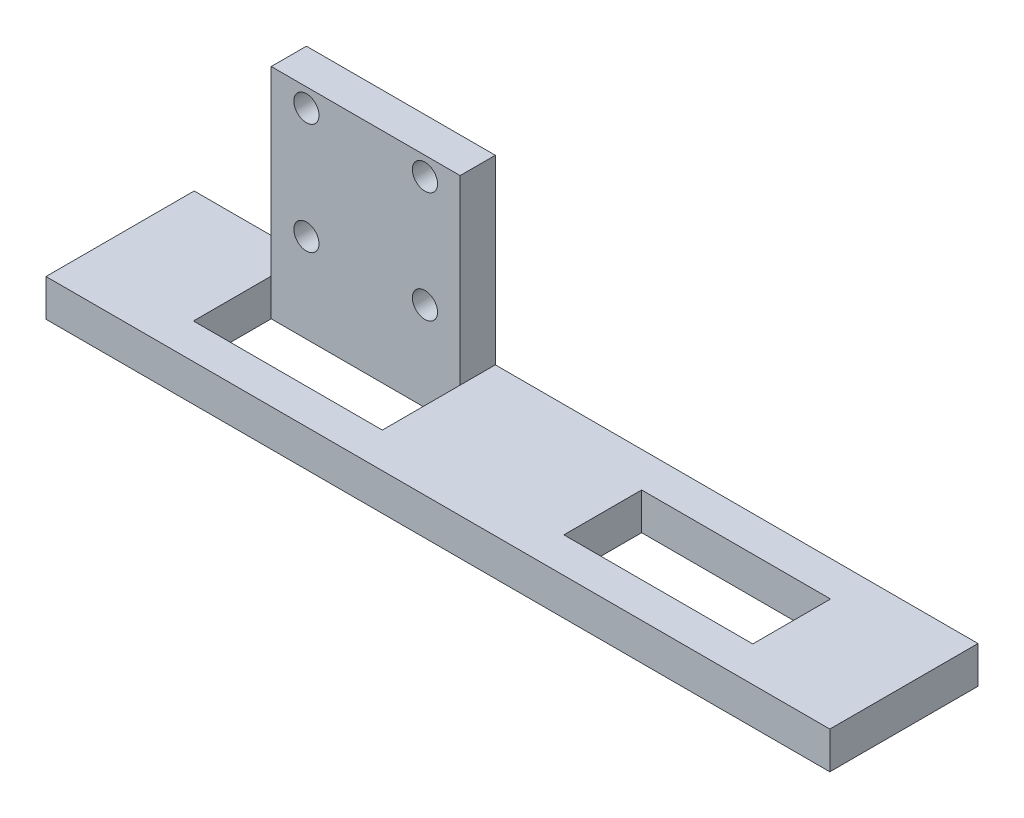
SolidWorks part; units mm, degrees
ref_plane "Front Plane" through (0, 0, 0) normal (0, 0, 1) x (1, 0, 0)
ref_plane "Top Plane" through (0, 0, 0) normal (0, 1, 0) x (1, 0, 0)
ref_plane "Right Plane" through (0, 0, 0) normal (1, 0, 0) x (0, 0, -1)
sketch "Sketch1" plane through (0, 0, 0) normal (0, 1, 0) x (1, 0, 0)
  line L0 (0, 10) -> (0, -10) construction
  line L1 (52.9, -10) -> (-52.9, -10)
  line L2 (52.9, -10) -> (52.9, 10)
  line L3 (52.9, 10) -> (-52.9, 10)
  line L4 (-52.9, -10) -> (-52.9, 10)
  line L5 (52.9, -10) -> (-52.9, 10) construction
  line L6 (52.9, 10) -> (-52.9, -10) construction
  line L7 (12.25, 5.25) -> (37.75, 5.25)
  line L8 (12.25, 5.25) -> (12.25, -5.25)
  line L9 (12.25, -5.25) -> (37.75, -5.25)
  line L10 (37.75, 5.25) -> (37.75, -5.25)
  line L11 (12.25, 5.25) -> (37.75, -5.25) construction
  line L12 (12.25, -5.25) -> (37.75, 5.25) construction
  line L13 (-37.75, 5.25) -> (-37.75, -5.25)
  line L14 (-12.25, 5.25) -> (-12.25, -5.25)
  line L15 (-12.25, 5.25) -> (-37.75, 5.25)
  line L16 (-12.25, -5.25) -> (-37.75, -5.25)
  point P0 (0, 0)
  point P6 (25, 0)
  dimension "D1" = 105.8
  dimension "D2" = 20
  dimension "D3" = 25.5
  dimension "D4" = 10.5
  dimension "D5" = 15.15
  dimension "D6" = 4.75
extrude "Boss-Extrude1" add sketch "Sketch1" along normal blind 5
sketch "Sketch2" plane through (0, 5, 0) normal (0, 1, 0) x (1, 0, 0)
  line L0 (52.9, 10) -> (-52.9, 10) construction
  line L1 (-37.75, 5.25) -> (-12.25, 5.25)
  line L2 (-37.75, 5.25) -> (-37.75, 10)
  line L3 (-37.75, 10) -> (-12.25, 10)
  line L4 (-12.25, 5.25) -> (-12.25, 10)
extrude "Boss-Extrude2" add sketch "Sketch2" along normal blind 24.5
sketch "Sketch3" plane through (0, 0, -10) normal (0, 0, -1) x (-1, 0, 0)
  line L0 (17, 27) -> (33, 27) construction
  line L1 (33, 27) -> (33, 12) construction
  line L2 (33, 12) -> (17, 12) construction
  line L3 (17, 12) -> (17, 27) construction
  line L4 (-52.9, 5) -> (12.25, 5) construction
  line L5 (25, 29.5) -> (25, 0) construction
  line L6 (12.25, 29.5) -> (37.75, 29.5) construction
  line L7 (-52.9, 0) -> (52.9, 0) construction
  circle A0 centre (33, 27) radius 1.7
  circle A1 centre (33, 12) radius 1.7
  circle A2 centre (17, 12) radius 1.7
  circle A3 centre (17, 27) radius 1.7
  point P16 (25, 12)
  dimension "D3" = 3.4
  dimension "D4" = 3.4
  dimension "D5" = 3.4
  dimension "D6" = 3.4
  dimension "D1" = 15
  dimension "D2" = 16
  dimension "D7" = 7
extrude "Cut-Extrude1" cut sketch "Sketch3" against normal blind 5
